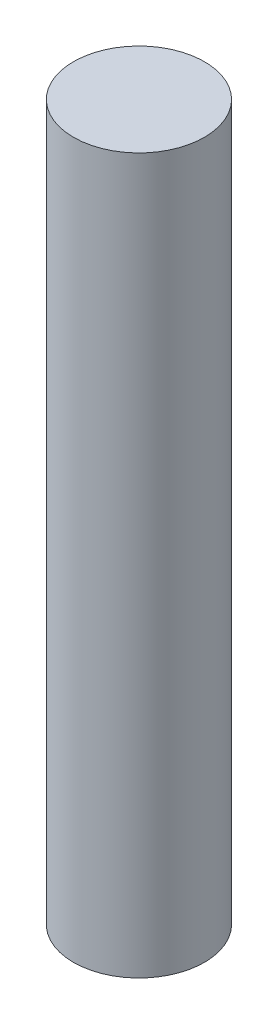
SolidWorks part; units mm, degrees
ref_plane "Front Plane" through (0, 0, 0) normal (0, 0, 1) x (1, 0, 0)
ref_plane "Top Plane" through (0, 0, 0) normal (0, 1, 0) x (1, 0, 0)
ref_plane "Right Plane" through (0, 0, 0) normal (1, 0, 0) x (0, 0, -1)
sketch "Sketch1" plane through (0, 0, 0) normal (0, 1, 0) x (1, 0, 0)
  circle A0 centre (0, 0) radius 27.5
  dimension "D1" = 55
extrude "Boss-Extrude1" add sketch "Sketch1" along normal blind 300
